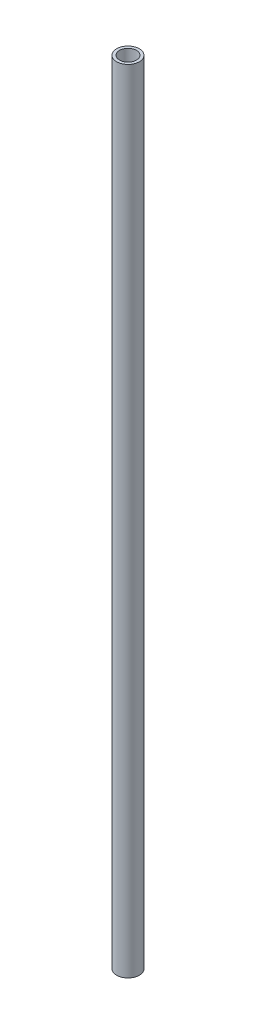
SolidWorks part; units mm, degrees
material "Thornel Mat VMA"
ref_plane "前视基准面" through (0, 0, 0) normal (0, 0, 1) x (1, 0, 0)
ref_plane "上视基准面" through (0, 0, 0) normal (0, 1, 0) x (1, 0, 0)
ref_plane "右视基准面" through (0, 0, 0) normal (1, 0, 0) x (0, 0, -1)
sketch "草图1" plane through (0, 0, 0) normal (0, 1, 0) x (1, 0, 0)
  circle A0 centre (0, 0) radius 4
  circle A1 centre (0, 0) radius 3
  dimension "D1" = 8
  dimension "D2" = 6
extrude "凸台-拉伸1" add sketch "草图1" along normal blind 280
